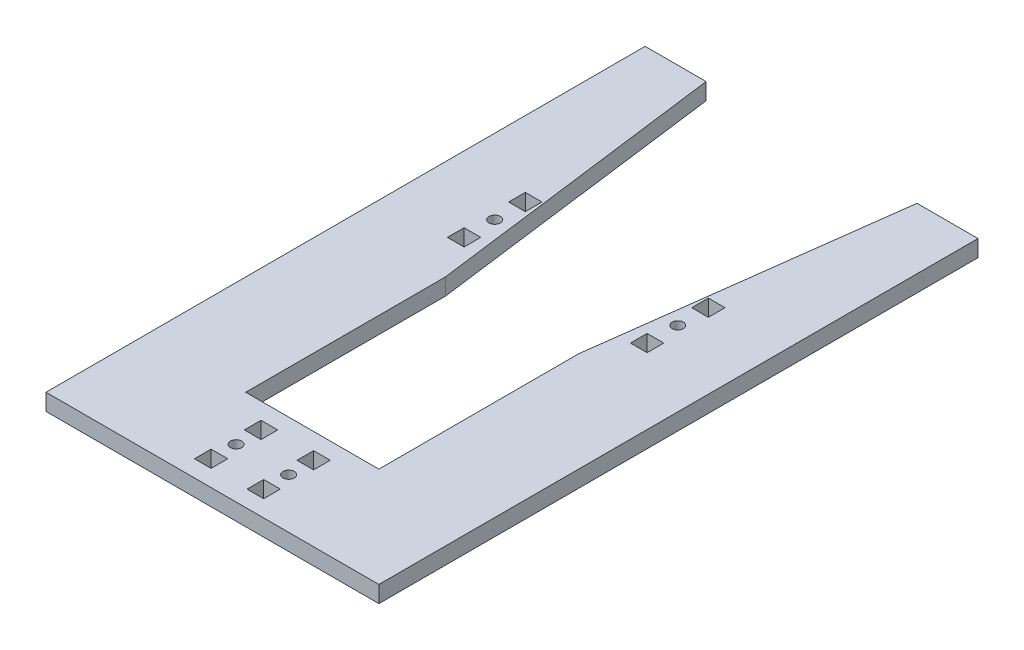
SolidWorks part; units mm, degrees
ref_plane "Front Plane" through (0, 0, 0) normal (0, 0, 1) x (1, 0, 0)
ref_plane "Top Plane" through (0, 0, 0) normal (0, 1, 0) x (1, 0, 0)
ref_plane "Right Plane" through (0, 0, 0) normal (1, 0, 0) x (0, 0, -1)
sketch "Bottom Plate" plane through (0, 0, 0) normal (0, 1, 0) x (1, 0, 0)
  line L0 (25.4, 0) -> (47.625, 171.3029)
  line L1 (-25.4, 0) -> (-47.625, 171.3029)
  line L2 (0, 0) -> (0, -177.8) construction
  line L3 (-25.4, 0) -> (-25.4, -76.2)
  line L4 (25.4, 0) -> (25.4, -76.2)
  line L5 (-25.4, 0) -> (25.4, 0) construction
  line L6 (-177.8, 0) -> (197.4825, 0) construction
  line L7 (125.3403, 80.518) -> (125.3403, -80.518) construction
  line L8 (131.6903, -50.8) -> (157.0903, -50.8)
  line L9 (131.6903, -50.8) -> (131.6903, 50.8)
  line L10 (131.6903, 50.8) -> (157.0903, 50.8)
  line L11 (157.0903, -50.8) -> (157.0903, 50.8)
  line L12 (131.6903, -50.8) -> (157.0903, 50.8) construction
  line L13 (131.6903, 50.8) -> (157.0903, -50.8) construction
  line L14 (-31.75, 36.83) -> (-31.75, 43.18)
  line L15 (31.75, 13.462) -> (38.1, 13.462)
  line L16 (38.1, 13.462) -> (38.1, 19.812)
  line L17 (38.1, 19.812) -> (31.75, 19.812)
  line L18 (31.75, 36.83) -> (38.1, 36.83)
  line L19 (38.1, 36.83) -> (38.1, 43.18)
  line L20 (125.3403, 72.009) -> (131.6903, 72.009) construction
  line L21 (131.6903, 50.8) -> (131.6903, 80.518) construction
  line L22 (131.6903, -50.8) -> (131.6903, -80.518) construction
  line L23 (125.3403, -63.5) -> (131.6903, -63.5)
  line L24 (125.3403, -63.5) -> (125.3403, -57.15)
  line L25 (125.3403, -57.15) -> (131.6903, -57.15)
  line L26 (131.6903, -63.5) -> (131.6903, -57.15)
  line L27 (125.3403, 63.5) -> (131.6903, 63.5)
  line L28 (131.6903, 63.5) -> (131.6903, 57.15)
  line L29 (125.3403, 63.5) -> (125.3403, 57.15)
  line L30 (125.3403, 57.15) -> (131.6903, 57.15)
  line L31 (-25.4, -76.2) -> (25.4, -76.2)
  line L32 (125.3403, 80.518) -> (131.6903, 80.518) construction
  line L33 (58.8162, 158.8529) -> (56.1364, 138.198) construction
  line L34 (52.5189, 159.6699) -> (58.8162, 158.8529)
  line L35 (52.5189, 159.6699) -> (53.3359, 165.9671)
  line L36 (53.3359, 165.9671) -> (59.6332, 165.1501)
  line L37 (56.4846, 165.5586) -> (52.9878, 138.6065) construction
  line L38 (58.8162, 158.8529) -> (59.6332, 165.1501)
  line L39 (52.5189, 159.6699) -> (59.6332, 165.1501) construction
  line L40 (53.3359, 165.9671) -> (58.8162, 158.8529) construction
  line L41 (56.1364, 138.198) -> (49.8392, 139.015) construction
  line L42 (49.8392, 139.015) -> (53.3359, 165.9671) construction
  line L43 (38.1, 43.18) -> (31.75, 43.18)
  line L44 (-31.75, 19.812) -> (-31.75, 13.462)
  line L45 (31.75, 19.812) -> (31.75, 13.462)
  line L46 (31.75, 36.83) -> (31.75, 43.18)
  line L47 (-38.1, 43.18) -> (-31.75, 43.18)
  line L48 (-38.1, 36.83) -> (-38.1, 43.18)
  line L49 (-31.75, 36.83) -> (-38.1, 36.83)
  line L50 (-38.1, 19.812) -> (-31.75, 19.812)
  line L51 (27.813, -127) -> (-27.813, -127) construction
  line L52 (-10.033, -82.55) -> (-10.033, -107.95) construction
  line L53 (-13.208, -82.55) -> (-6.858, -82.55)
  line L54 (-13.208, -82.55) -> (-13.208, -88.9)
  line L55 (-13.208, -88.9) -> (-6.858, -88.9)
  line L56 (-6.858, -82.55) -> (-6.858, -88.9)
  line L57 (-6.858, -101.6) -> (-13.208, -101.6)
  line L58 (-6.858, -101.6) -> (-6.858, -107.95)
  line L59 (-6.858, -107.95) -> (-13.208, -107.95)
  line L60 (-13.208, -101.6) -> (-13.208, -107.95)
  line L61 (10.033, -82.55) -> (10.033, -107.95) construction
  line L62 (-38.1, 13.462) -> (-38.1, 19.812)
  line L63 (13.208, -101.6) -> (13.208, -107.95)
  line L64 (6.858, -107.95) -> (13.208, -107.95)
  line L65 (6.858, -101.6) -> (6.858, -107.95)
  line L66 (6.858, -101.6) -> (13.208, -101.6)
  line L67 (6.858, -82.55) -> (6.858, -88.9)
  line L68 (13.208, -88.9) -> (6.858, -88.9)
  line L69 (13.208, -82.55) -> (13.208, -88.9)
  line L70 (13.208, -82.55) -> (6.858, -82.55)
  line L71 (-31.75, 13.462) -> (-38.1, 13.462)
  line L73 (125.3403, -80.518) -> (131.6903, -80.518) construction
  line L84 (-131.6903, 50.8) -> (-157.0903, -50.8) construction
  line L85 (-131.6903, -50.8) -> (-157.0903, 50.8) construction
  line L86 (-157.0903, -50.8) -> (-157.0903, 50.8)
  line L87 (-131.6903, -50.8) -> (-131.6903, 50.8)
  line L88 (-131.6903, -63.5) -> (-131.6903, -57.15)
  line L89 (-125.3403, -57.15) -> (-131.6903, -57.15)
  line L90 (-125.3403, -63.5) -> (-125.3403, -57.15)
  line L91 (-125.3403, -63.5) -> (-131.6903, -63.5)
  line L92 (-131.6903, -50.8) -> (-157.0903, -50.8)
  line L93 (-131.6903, 50.8) -> (-157.0903, 50.8)
  line L94 (-125.3403, 57.15) -> (-131.6903, 57.15)
  line L95 (-125.3403, 63.5) -> (-125.3403, 57.15)
  line L96 (-131.6903, 63.5) -> (-131.6903, 57.15)
  line L99 (-125.3403, 63.5) -> (-131.6903, 63.5)
  line L101 (-53.3359, 165.9671) -> (-58.8162, 158.8529) construction
  line L102 (-52.5189, 159.6699) -> (-59.6332, 165.1501) construction
  line L103 (-58.8162, 158.8529) -> (-59.6332, 165.1501)
  line L104 (-53.3359, 165.9671) -> (-59.6332, 165.1501)
  line L105 (-52.5189, 159.6699) -> (-53.3359, 165.9671)
  line L106 (-52.5189, 159.6699) -> (-58.8162, 158.8529)
  arc A0 (-47.625, 171.3029) -> (47.625, 171.3029) centre (0, 0) ccw
  circle A1 centre (128.5153, 72.009) radius 2.159
  circle A2 centre (128.5153, -72.009) radius 2.159
  circle A3 centre (54.0826, 147.0448) radius 2.159
  circle A4 centre (34.925, 28.321) radius 2.159
  circle A5 centre (-10.033, -95.25) radius 2.159
  circle A6 centre (27.813, -127) radius 2.794
  circle A7 centre (-27.813, -127) radius 2.794
  circle A8 centre (10.033, -95.25) radius 2.159
  circle A9 centre (-34.925, 28.321) radius 2.159
  circle A10 centre (-128.5153, -72.009) radius 2.159
  circle A11 centre (-128.5153, 72.009) radius 2.159
  circle A12 centre (-54.0826, 147.0448) radius 2.159
  point P2 (56.0761, 162.41)
  point P13 (144.3903, 0)
  point P74 (0, -127)
  point P90 (34.925, 19.812)
  point P106 (-144.3903, 0)
  point P129 (-56.0761, 162.41)
  dimension "D1" = 355.6
  dimension "D11" = 4.318
  dimension "D12" = 6.35
  dimension "D14" = 6.35
  dimension "D17" = 6.35
  dimension "D20" = 4.318
  dimension "D21" = 6.35
  dimension "D24" = 6.35
  dimension "D28" = 6.35
  dimension "D35" = 4.318
  dimension "D15" = 5.588
  dimension "D36" = 5.588
  dimension "D27" = 6.35
  dimension "D23" = 4.318
  dimension "D39" = 6.35
  dimension "D4" = 101.6
  dimension "D5" = 25.4
  dimension "D6" = 12.7
  dimension "D7" = 89.662
  dimension "D8" = 6.35
  dimension "D9" = 6.35
  dimension "D10" = 6.35
  dimension "D13" = 6.35
  dimension "D16" = 6.35
  dimension "D18" = 6.35
  dimension "D19" = 6.35
  dimension "D22" = 10.16
  dimension "D25" = 6.35
  dimension "D26" = 95.25
  dimension "D29" = 6.35
  dimension "D30" = 6.35
  dimension "D31" = 6.35
  dimension "D32" = 12.7
  dimension "D33" = 6.35
  dimension "D34" = 6.35
  dimension "D37" = 55.626
  dimension "D38" = 50.8
  dimension "D40" = 6.858
  dimension "D41" = 50.8
  dimension "D42" = 76.2
  dimension "D43" = 13.208
extrude "Boss-Extrude1" add sketch "Bottom Plate" against normal blind 6.35
sketch "Sketch1" plane through (0, 0, 0) normal (0, 1, 0) x (1, 0, 0)
  line L1 (-63.5, -114.3) -> (63.5, -114.3)
  line L2 (-63.5, -114.3) -> (-63.5, 114.3)
  line L3 (-63.5, 114.3) -> (63.5, 114.3)
  line L4 (63.5, -114.3) -> (63.5, 114.3)
  line L5 (-63.5, -114.3) -> (63.5, 114.3) construction
  line L6 (-63.5, 114.3) -> (63.5, -114.3) construction
  line L7 (-254, -254) -> (254, -254)
  line L8 (-254, -254) -> (-254, 254)
  line L9 (-254, 254) -> (254, 254)
  line L10 (254, -254) -> (254, 254)
  line L11 (-254, -254) -> (254, 254) construction
  line L12 (-254, 254) -> (254, -254) construction
  point P0 (0, 0)
  point P6 (0, 0)
  dimension "D1" = 228.6
  dimension "D2" = 127
  dimension "D3" = 508
  dimension "D4" = 508
extrude "Cut-Extrude1" cut sketch "Sketch1" against normal blind 25.4
equation "\"Ball Diameter\"= 1.75in"
equation "\"Sheet Thickness\"= 0.25in"
equation "\"D13@Bottom Plate\" = \"Sheet Thickness\""
equation "\"D10@Bottom Plate\"=\"Sheet Thickness\""
equation "\"Screw Diameter\"= .17in"
equation "\"D11@Bottom Plate\"=\"Screw Diameter\""
equation "\"Robot Diameter\"= 14in"
equation "\"D1@Bottom Plate\"=\"Robot Diameter\""
equation "\"D16@Bottom Plate\"=\"Sheet Thickness\""
equation "\"D18@Bottom Plate\"=\"Sheet Thickness\""
equation "\"D20@Bottom Plate\"=\"Screw Diameter\""
equation "\"D29@Bottom Plate\"=\"Sheet Thickness\""
equation "\"D30@Bottom Plate\"=\"Sheet Thickness\""
equation "\"D33@Bottom Plate\" = \"Sheet Thickness\""
equation "\"D34@Bottom Plate\"=\"Sheet Thickness\""
equation "\"D35@Bottom Plate\"=\"Screw Diameter\""
equation "\"Castor Screw Diameter\"= 0.22in"
equation "\"D15@Bottom Plate\"=\"Castor Screw Diameter\""
equation "\"D36@Bottom Plate\"=\"Castor Screw Diameter\""
equation "\"Wheel Diameter\" = 4in"
equation "\"D4@Bottom Plate\"=\"Wheel Diameter\""
equation "\"Nut Diameter\" = 8.4mm"
equation "\"Nut Height\" = 2.9mm"
equation "\"Screw Height\" = 0.55in"
equation "\"Pulley Diameter\" = 1in"
equation "\"Reactor Height\" = 14in"
equation "\"Elevator Height\" = 11.5in"
equation "\"Elevator Width\" = \"Ball Diameter\" + 0.25in"
equation "\"Elevator Bearing Diameter\" = sqr(2*(\"Sheet Thickness\"^2)) + 0.2in"
equation "\"Elevator Axle Length\" = \"Elevator Width\" + 8*\"Sheet Thickness\""
equation "\"D41@Bottom Plate\"=\"Elevator Width\""
equation "\"D8@Bottom Plate\"=\"Sheet Thickness\""
equation "\"D23@Bottom Plate\"=\"Screw Diameter\""
equation "\"D24@Bottom Plate\"=\"Sheet Thickness\""
equation "\"D9@Bottom Plate\"=\"Sheet Thickness\""
equation "\"D25@Bottom Plate\"=\"Sheet Thickness\""
equation "\"D19@Bottom Plate\"=\"Sheet Thickness\""
equation "\"D27@Bottom Plate\"=\"Sheet Thickness\""
equation "\"D7@Bottom Plate\"=(\"Elevator Clearance from Axis\") + 1in - (\"Pulley Diameter\"/2 + \"Sheet Thickness\")"
equation "\"D28@Bottom Plate\"=\"Sheet Thickness\""
equation "\"D39@Bottom Plate\"=\"Sheet Thickness\""
equation "\"Elevator Axle Endcap Diameter\" = \"Pulley Diameter\" + 0.25in"
equation "\"Elevator Clearance from Axis\" = 3.28in"
